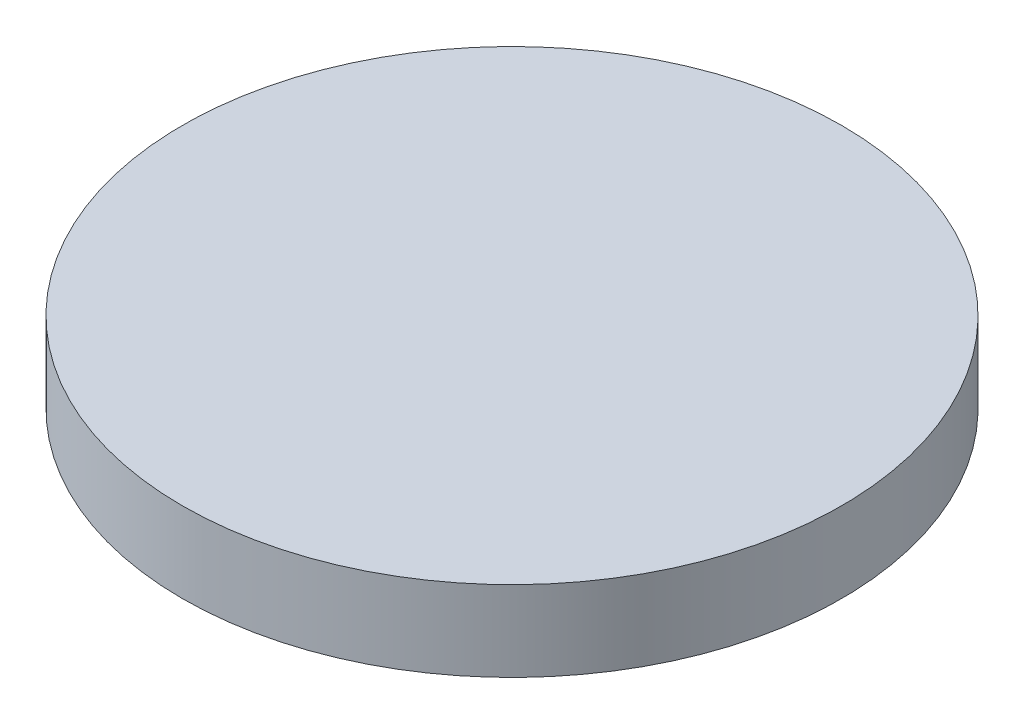
SolidWorks part; units mm, degrees
ref_plane "Front Plane" through (0, 0, 0) normal (0, 0, 1) x (1, 0, 0)
ref_plane "Top Plane" through (0, 0, 0) normal (0, 1, 0) x (1, 0, 0)
ref_plane "Right Plane" through (0, 0, 0) normal (1, 0, 0) x (0, 0, -1)
sketch "Sketch1" plane through (0, 0, 0) normal (0, 1, 0) x (1, 0, 0)
  circle A0 centre (0, 0) radius 20.5
  dimension "D1" = 41
extrude "Boss-Extrude1" add sketch "Sketch1" along normal blind 5
